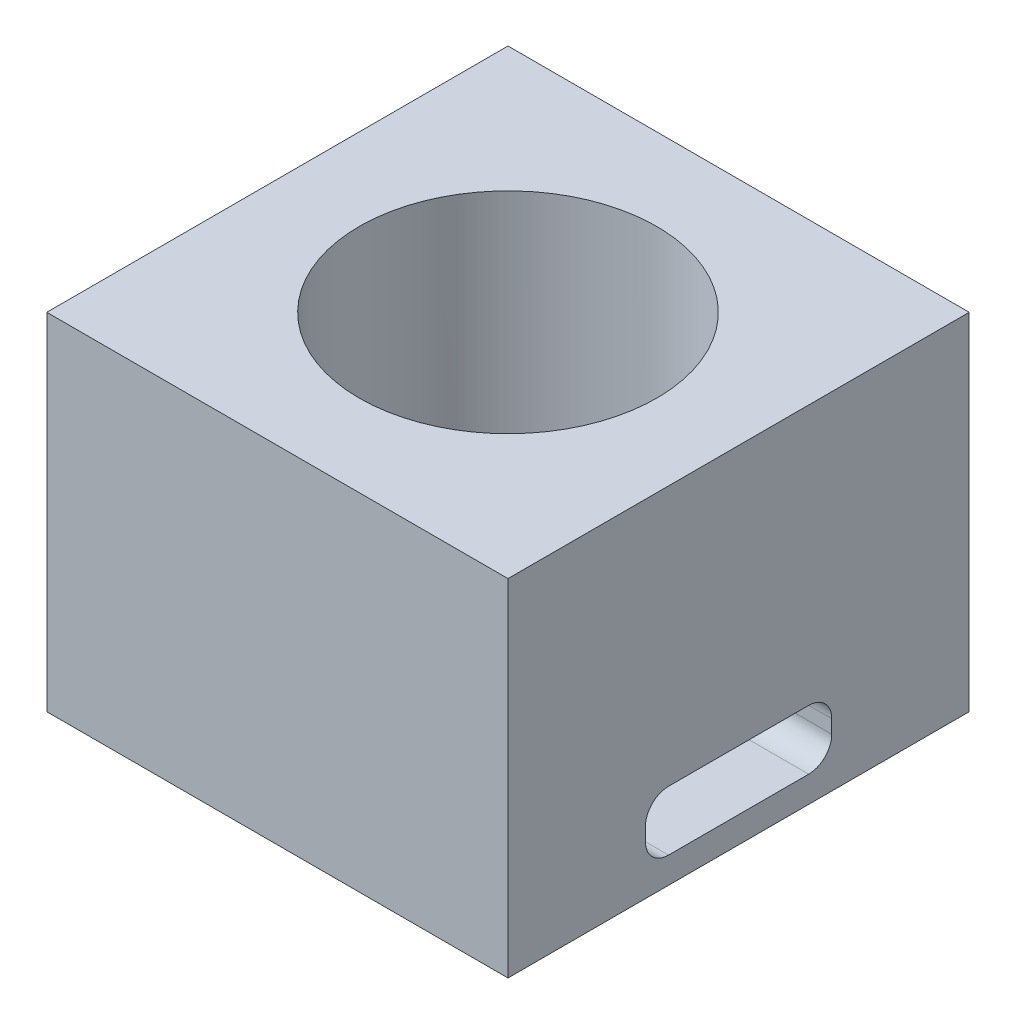
SolidWorks part; units mm, degrees
ref_plane "Front Plane" through (0, 0, 0) normal (0, 0, 1) x (1, 0, 0)
ref_plane "Top Plane" through (0, 0, 0) normal (0, 1, 0) x (1, 0, 0)
ref_plane "Right Plane" through (0, 0, 0) normal (1, 0, 0) x (0, 0, -1)
sketch "Sketch1" plane through (0, 0, 0) normal (0, 1, 0) x (1, 0, 0)
  line L1 (-25.4, -25.4) -> (25.4, -25.4)
  line L2 (-25.4, -25.4) -> (-25.4, 25.4)
  line L3 (-25.4, 25.4) -> (25.4, 25.4)
  line L4 (25.4, -25.4) -> (25.4, 25.4)
  line L5 (-25.4, -25.4) -> (25.4, 25.4) construction
  line L6 (-25.4, 25.4) -> (25.4, -25.4) construction
  point P0 (0, 0)
  dimension "D1" = 50.8
  dimension "D2" = 50.8
extrude "Boss-Extrude1" add sketch "Sketch1" along normal blind 38.1
sketch "Sketch2" plane through (0, 38.1, 0) normal (0, 1, 0) x (1, 0, 0)
  circle A0 centre (0, 0) radius 16.383
  dimension "D1" = 32.766
extrude "Cut-Extrude1" cut sketch "Sketch2" against normal blind 49.53
sketch "Sketch3" plane through (25.4, 0, 0) normal (1, 0, 0) x (0, 0, -1)
  line L1 (-7.7181, 9.4456) -> (7.7181, 9.4456)
  line L2 (-10.2581, 6.9056) -> (-10.2581, 5.4246)
  line L3 (-7.7181, 2.8846) -> (7.7181, 2.8846)
  line L4 (10.2581, 6.9056) -> (10.2581, 5.4246)
  line L5 (-10.2581, 9.4456) -> (10.2581, 2.8846) construction
  line L6 (-10.2581, 2.8846) -> (10.2581, 9.4456) construction
  arc A0 (7.7181, 9.4456) -> (10.2581, 6.9056) centre (7.7181, 6.9056) cw
  arc A1 (10.2581, 5.4246) -> (7.7181, 2.8846) centre (7.7181, 5.4246) cw
  arc A2 (-7.7181, 2.8846) -> (-10.2581, 5.4246) centre (-7.7181, 5.4246) cw
  arc A3 (-7.7181, 9.4456) -> (-10.2581, 6.9056) centre (-7.7181, 6.9056) ccw
  point P0 (0, 6.1651)
  dimension "D1" = 2.54
extrude "Cut-Extrude2" cut sketch "Sketch3" against normal blind 29.21
